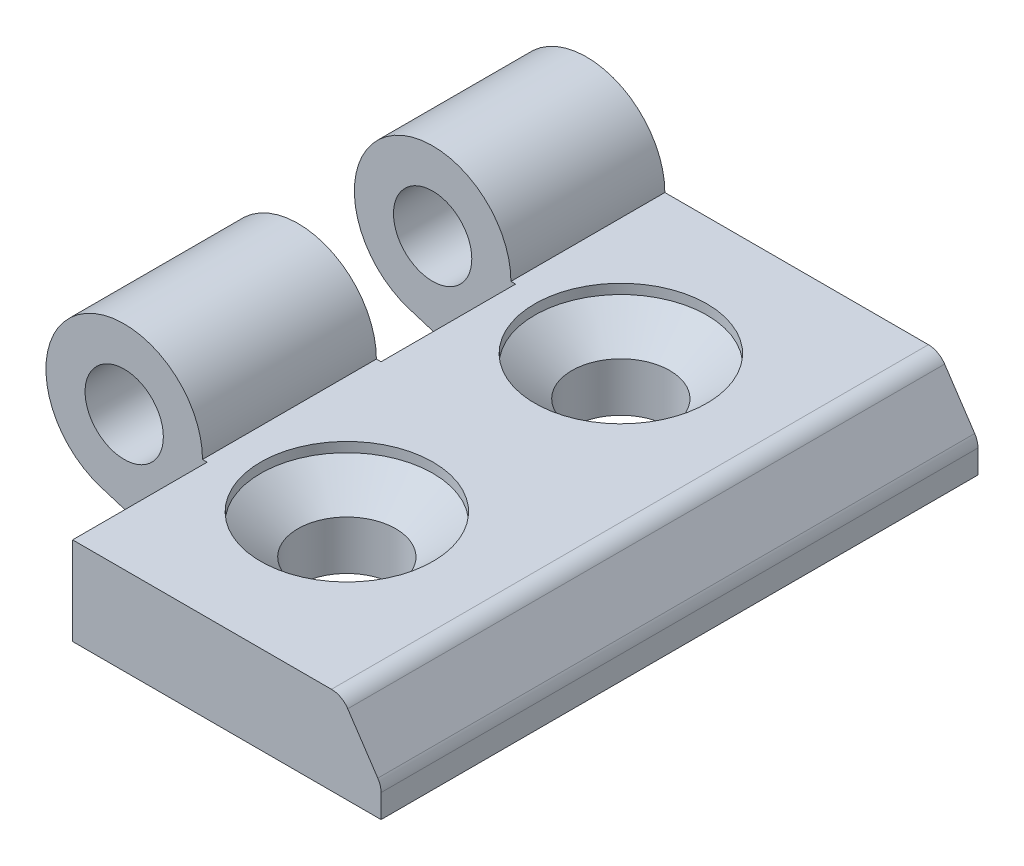
SolidWorks part; units mm, degrees
ref_plane "前视基准面" through (0, 0, 0) normal (0, 0, 1) x (1, 0, 0)
ref_plane "上视基准面" through (0, 0, 0) normal (0, 1, 0) x (1, 0, 0)
ref_plane "右视基准面" through (0, 0, 0) normal (1, 0, 0) x (0, 0, -1)
sketch "草图1" plane through (0, 0, 0) normal (0, 0, 1) x (1, 0, 0)
  line B0 (20, -4.5) -> (1, -4.5)
  line B1 (20, -3.3028) -> (20, -4.5)
  line B2 (20, -4.5) -> (1, -4.5)
  line B3 (17.4648, 0) -> (4, 0)
  line B4 (19.8321, -2.7481) -> (18.2969, -0.4453)
  line B5 (1, -4.5) -> (-1.1879, -3.8195)
  arc B6 (20, -3.3028) -> (19.8321, -2.7481) centre (19, -3.3028) ccw
  arc B7 (18.2969, -0.4453) -> (17.4648, 0) centre (17.4648, -1) ccw
  arc B8 (4, 0) -> (-1.1879, -3.8195) centre (0, 0) ccw
sketch_block_instance "A$C03935E30-1"
sketch_block "A$C03935E30"
extrude "凸台-拉伸1" add sketch "草图1" along normal mid plane 30.5 contours B3 B8 B5 B0 B1 B6 B4 B7
sketch "草图3" plane through (0, 0, 0) normal (0, 1, 0) x (1, 0, 0)
  line L1 (-4, -15.25) -> (4.2382, -15.25)
  line L2 (-4, -15.25) -> (-4, -8.375)
  line L3 (-4, -8.375) -> (4.2382, -8.375)
  line L4 (4.2382, -15.25) -> (4.2382, -8.375)
  line L8 (-4, 0.51) -> (4.2382, 0.51)
  line L9 (-4, 0.51) -> (-4, 7.385)
  line L10 (-4, 7.385) -> (4.2382, 7.385)
  line L11 (4.2382, 0.51) -> (4.2382, 7.385)
  line L16 (-4, 8.39) -> (4.2382, 8.39) [skipped]
  line L17 (-4, 8.39) -> (-4, 15.265) [skipped]
  line L18 (-4, 15.265) -> (4.2382, 15.265) [skipped]
  line L19 (4.2382, 8.39) -> (4.2382, 15.265) [skipped]
  line L20 (-4, -7.37) -> (4.2382, -7.37) [skipped]
  line L21 (-4, -7.37) -> (-4, -0.495) [skipped]
  line L22 (-4, -0.495) -> (4.2382, -0.495) [skipped]
  line L23 (4.2382, -7.37) -> (4.2382, -0.495) [skipped]
  dimension "D1" = 6.875
  dimension "D2" = 4
extrude "切除-拉伸1" cut sketch "草图3" against normal through all and the other way through all
sketch "草图4" plane through (0, 0, 8.375) normal (0, 0, 1) x (1, 0, 0)
  circle A0 centre (0, 0) radius 2
extrude "切除-拉伸2" cut sketch "草图4" against normal through all
ref_plane "基准面2" through (0, 0, 7) normal (0, 0, 1) x (1, 0, 0)
sketch "草图5" plane through (0, 0, 7) normal (0, 0, 1) x (1, 0, 0)
  line L0 (10, -4.5) -> (10, 0)
  line L1 (20, -4.5) -> (4.2382, -4.5) construction
  line L2 (17.4648, 0) -> (4.2382, 0) construction
  line L3 (10, 0) -> (14.4, 0)
  line L4 (10, -4.5) -> (12.5, -4.5)
  line L5 (14.4, 0) -> (14.4, -0.5)
  line L6 (12.5, -4.5) -> (12.5, -2)
  line L7 (12.5, -2) -> (14.4, -0.5)
  circle A0 centre (0, 0) radius 2 construction
  dimension "D1" = 10
revolve "切除-旋转1" cut sketch "草图5" angle 360 about L0
pattern_linear "阵列(线性)1" count 2 spacing 14 along (0, 0, -1) of "切除-旋转1"
